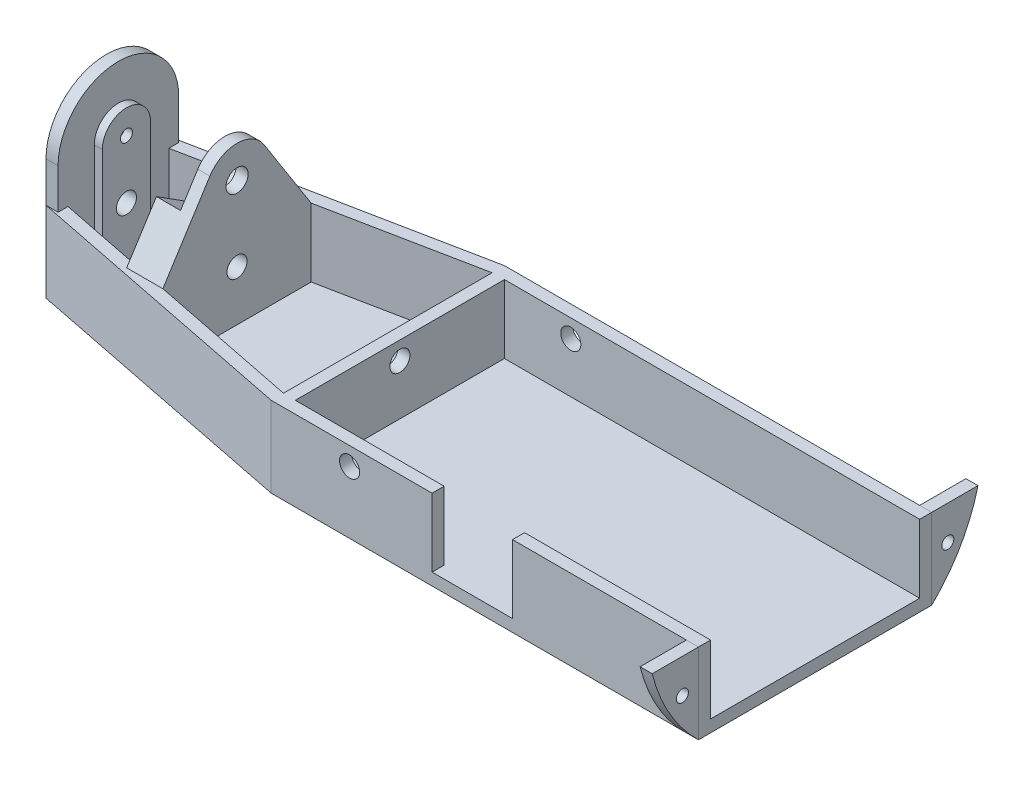
SolidWorks part; units mm, degrees
ref_plane "Front Plane" through (0, 0, 0) normal (0, 0, 1) x (1, 0, 0)
ref_plane "Top Plane" through (0, 0, 0) normal (0, 1, 0) x (1, 0, 0)
ref_plane "Right Plane" through (0, 0, 0) normal (1, 0, 0) x (0, 0, -1)
sketch "Sketch2" plane through (0, 0, 0) normal (0, 1, 0) x (1, 0, 0)
  line L0 (-119.25, 15) -> (-119.25, -15)
  line L1 (-49.25, -29) -> (57, -29)
  line L2 (-49.25, -29) -> (-49.25, 29)
  line L3 (-49.25, 29) -> (57, 29)
  line L4 (57, -29) -> (57, 29)
  line L6 (60, 12) -> (60, -39) construction
  line L7 (-119.25, -15) -> (-49.25, -29)
  line L8 (-119.25, 15) -> (-49.25, 29)
  line L9 (-46.25, -23.4) -> (-46.25, 23.4) construction
  line L10 (-46.25, 23.4) -> (-46.25, -23.4) construction
  point P0 (0, 0)
  point P8 (-49.25, 0)
  point P9 (-119.25, 0)
  point P14 (-46.25, 0)
  point P15 (0, 0)
  dimension "D1" = 3
  dimension "D2" = 58
  dimension "D3" = 30
  dimension "D4" = 70
  dimension "D5" = 3
extrude "Boss-Extrude1" add sketch "Sketch2" along normal blind 3 contours L8 L0 L7 L2 | L1 L4 L3 L2
sketch "Sketch3" plane through (0, 0, 0) normal (0, -1, 0) x (1, 0, 0)
  line L0 (-49.25, -29) -> (57, -29) construction
  line L1 (-49.25, 29) -> (-46.25, 29)
  line L2 (-49.25, 29) -> (-49.25, -29)
  line L3 (-49.25, -29) -> (-46.25, -29)
  line L4 (-46.25, 29) -> (-46.25, -29)
  line L5 (57, 29) -> (57, -29) construction
  line L6 (-46.25, 29) -> (57, 29)
  line L7 (-46.25, 29) -> (-46.25, 26)
  line L8 (-46.25, 26) -> (57, 26)
  line L9 (57, 29) -> (57, 26)
  line L10 (-119.25, 15) -> (-49.25, 29) construction
  line L11 (57, -29) -> (-46.25, -29)
  line L12 (57, -29) -> (57, -26)
  line L13 (57, -26) -> (-46.25, -26)
  line L14 (-46.25, -29) -> (-46.25, -26)
  line L15 (-119.25, -11.9406) -> (-49.25, -25.9406)
  line L16 (-119.25, -15) -> (-49.25, -29) construction
  line L17 (-119.25, -15) -> (-119.25, 15) construction
  line L18 (-119.25, 11.9406) -> (-119.25, 15)
  line L19 (-119.25, 15) -> (-49.25, 29)
  line L20 (-49.25, 29) -> (-49.25, 25.9406)
  line L21 (-119.25, -11.9406) -> (-119.25, -15)
  line L22 (-119.25, -15) -> (-49.25, -29)
  line L23 (-49.25, -25.9406) -> (-49.25, -29)
  line L29 (-119.25, 11.9406) -> (-49.25, 25.9406)
  line M3 (-49.25, -29) -> (57, -29)
  line M4 (57, -29) -> (57, 29)
  line M5 (57, 29) -> (-49.25, 29)
  dimension "D1" = 3
  dimension "D2" = 3
  dimension "D3" = 3
  dimension "D4" = 3
  dimension "D5" = 3
extrude "Boss-Extrude2" add sketch "Sketch3" against normal blind 20 contours L4 L8 M4 M5 | L4 L2 M5 M3 | L13 L4 M4 M3
sketch "Sketch4" plane through (0, 0, 0) normal (0, -1, 0) x (1, 0, 0)
  line L0 (-119.25, -15) -> (-119.25, 15)
  line L1 (-119.25, -15) -> (-116.25, -15)
  line L2 (-119.25, 15) -> (-116.25, 15)
  line L3 (-116.25, -15) -> (-116.25, 15)
  dimension "D1" = 3
extrude "Boss-Extrude3" add sketch "Sketch4" against normal blind 30
sketch "Sketch5" plane through (0, 3, 0) normal (0, 1, 0) x (1, 0, 0)
  line L0 (-49.25, 25.9406) -> (-116.25, 12.5406)
  line L1 (-49.25, 29) -> (-49.25, -29) construction
  line L2 (-116.25, -15) -> (-116.25, 15) construction
  line L3 (-116.25, 12.5406) -> (-119.25, 15)
  line L4 (-119.25, 15) -> (-49.25, 29)
  line L5 (-49.25, 29) -> (-49.25, 25.9406)
  line L6 (-49.25, -25.9406) -> (-116.25, -12.5406)
  line L7 (-116.25, -12.5406) -> (-119.25, -15)
  line L8 (-119.25, -15) -> (-49.25, -29)
  line L9 (-49.25, -29) -> (-49.25, -25.9406)
  dimension "D1" = 3
  dimension "D2" = 3
extrude "Boss-Extrude4" add sketch "Sketch5" along normal up to surface (17 mm away) up to face at (4.625, 20, 0)
sketch "Sketch6" plane through (-119.25, 0, 0) normal (-1, 0, 0) x (0, 0, 1)
  line L0 (15, 30) -> (-15, 30) construction
  circle A0 centre (0, 30) radius 15
extrude "Boss-Extrude5" add sketch "Sketch6" against normal up to surface (3 mm away) up to face at (-116.25, 18.25, 0)
sketch "Sketch7" plane through (-119.25, 0, 0) normal (-1, 0, 0) x (0, 0, 1)
  circle A0 centre (0, 30) radius 3.1
  point P21 (0, 30)
  dimension "D1" = 6.2
extrude "Cut-Extrude1" cut sketch "Sketch7" against normal up to next
sketch "Sketch19" plane through (-116.25, 0, 0) normal (1, 0, 0) x (0, 0, -1)
  line L1 (-6, 30) -> (-6, 0.329)
  line L2 (6, 30) -> (6, 0.329)
  line L3 (-6, 0.329) -> (6, 0.329)
  arc A0 (6, 30) -> (-6, 30) centre (0, 30) ccw
  circle A1 centre (0, 30) radius 1.5
  dimension "D1" = 12
  dimension "D2" = 3
extrude "Boss-Extrude9" add sketch "Sketch19" along normal blind 2
sketch "Sketch11" plane through (0, 3, 0) normal (0, 1, 0) x (1, 0, 0)
  line L0 (-86.75, 18.4406) -> (-86.75, -18.4406)
  line L1 (-116.25, 12.5406) -> (-49.25, 25.9406) construction
  line L2 (-49.25, -25.9406) -> (-116.25, -12.5406) construction
  line L3 (-86.75, 7.5664) -> (-86.75, -7.5664) construction
  line L4 (-95.75, 16.6406) -> (-95.75, -16.6406)
  line L5 (-95.75, 16.6406) -> (-86.75, 18.4406)
  line L6 (-95.75, -16.6406) -> (-86.75, -18.4406)
  dimension "D1" = 9
extrude "Boss-Extrude6" add sketch "Sketch11" along normal up to surface (17 mm away) up to face at (-47.8125, 20, 0)
sketch "Sketch9" plane through (-119.25, 0, 0) normal (-1, 0, 0) x (0, 0, 1)
  line L0 (-15, 0) -> (15, 0) construction
  circle A0 centre (0, 15.5) radius 2.5
  point P4 (0, 0)
  dimension "D1" = 5
  dimension "D2" = 15.5
extrude "Cut-Extrude2" cut sketch "Sketch9" against normal through all
sketch "Sketch10" plane through (0, 0, 29) normal (0, 0, 1) x (1, 0, 0)
  circle A0 centre (-29.75, 15.5) radius 2.5
  dimension "D1" = 5
extrude "Cut-Extrude3" cut sketch "Sketch10" against normal through all both and the other way through all
sketch "Sketch14" plane through (-86.75, 0, 0) normal (1, 0, 0) x (0, 0, -1)
  line L0 (-18.4406, 20) -> (-6.7517, 38.3912)
  line L1 (18.4406, 20) -> (6.7517, 38.3912)
  circle A0 centre (0, 34.1) radius 2.75
  arc A1 (6.7517, 38.3912) -> (-6.7517, 38.3912) centre (0, 34.1) ccw
  line M4 (18.4406, 20) -> (-18.4406, 20)
  dimension "D1" = 5.5
  dimension "D2" = 16
extrude "Boss-Extrude7" add sketch "Sketch14" against normal up to surface (9 mm away) contours L1 A1 L0 A0 M4 up to face at (-95.75, 15.5, -2.5)
sketch "Sketch16" plane through (57, 0, 0) normal (1, 0, 0) x (0, 0, -1)
  line L0 (-29, 20) -> (-40.5093, 20)
  line L1 (-29, 0) -> (-29, 20)
  line L2 (29, 20) -> (40.5093, 20)
  line L3 (29, 0) -> (29, 20)
  arc A0 (-40.5093, 20) -> (-29, 0) centre (0, 30) ccw
  circle A1 centre (-33, 11.5) radius 1.5 construction
  arc A2 (29, 0) -> (40.5093, 20) centre (0, 30) ccw
  circle A3 centre (-33, 11.5) radius 1.5
  circle A5 centre (33, 11.5) radius 1.5
  circle A7 centre (33, 11.5) radius 1.5 construction
extrude "Boss-Extrude8" add sketch "Sketch16" against normal blind 3 separate body
sketch "Sketch17" plane through (-95.75, 0, 0) normal (-1, 0, 0) x (0, 0, 1)
  line L0 (4.2912, 27.3483) -> (11.0429, 31.6395)
  line L1 (6.7517, 38.3912) -> (18.4406, 20) construction
  line L2 (-11.0429, 31.6395) -> (-4.2912, 27.3483)
  line L3 (-6.7517, 38.3912) -> (-18.4406, 20) construction
  line L4 (11.0429, 31.6395) -> (6.7517, 38.3912)
  line L5 (-11.0429, 31.6395) -> (-6.7517, 38.3912)
  arc A0 (-4.2912, 27.3483) -> (4.2912, 27.3483) centre (0, 34.1) ccw
  arc A1 (6.7517, 38.3912) -> (-6.7517, 38.3912) centre (0, 34.1) ccw construction
  arc A2 (6.7517, 38.3912) -> (-6.7517, 38.3912) centre (0, 34.1) ccw
extrude "Cut-Extrude4" cut sketch "Sketch17" against normal offset from surface (6 mm away) 3 up to face at (-86.75, 15.5, 2.5)
sketch "Sketch18" plane through (0, 0, 29) normal (0, 0, 1) x (1, 0, 0)
  line L0 (57, 20) -> (-49.25, 20) construction
  line L1 (10.75, 20) -> (-9.25, 20)
  line L2 (10.75, 20) -> (10.75, 3)
  line L3 (10.75, 3) -> (-9.25, 3)
  line L4 (-9.25, 20) -> (-9.25, 3)
  line L5 (10.75, 5.4) -> (10.75, 17.4) construction
  line L6 (-49.25, 0) -> (57, 0) construction
  dimension "D1" = 20
  dimension "D2" = 3
extrude "Cut-Extrude5" cut sketch "Sketch18" against normal up to next (3 mm away)
